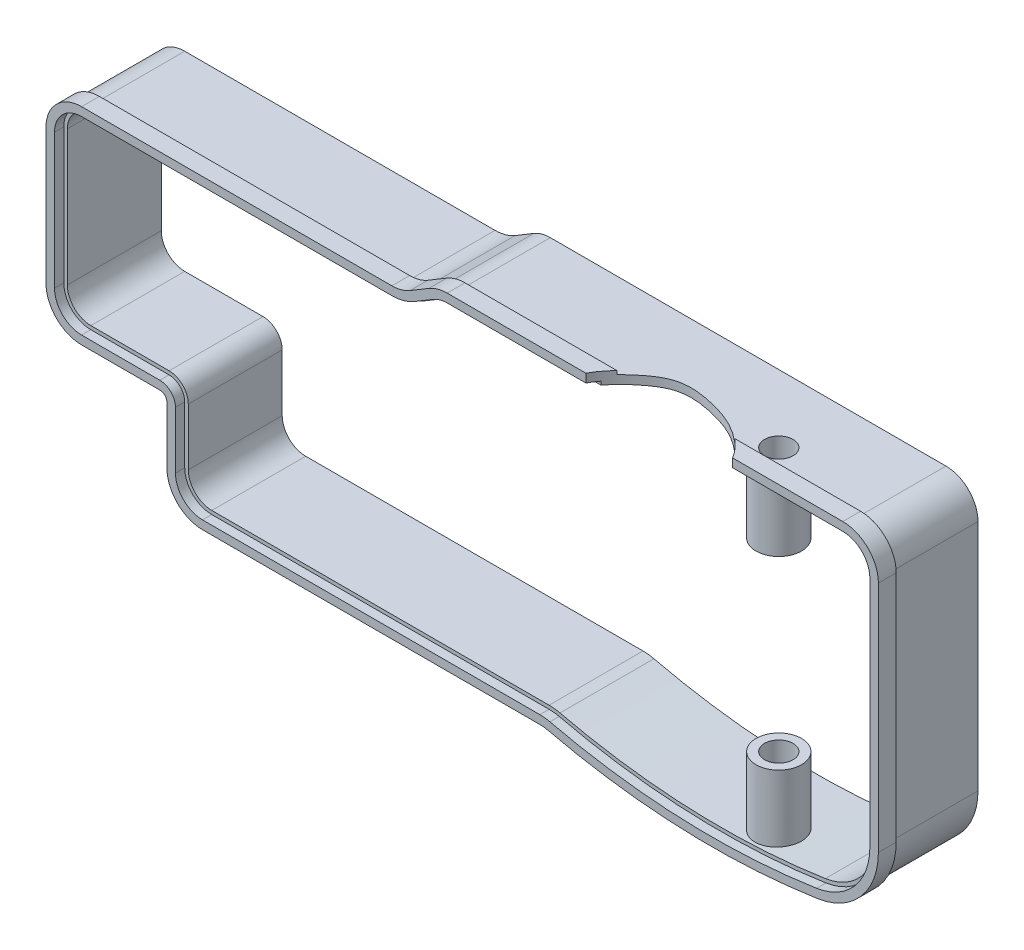
SolidWorks part; units mm, degrees
ref_plane "前视基准面" through (0, 0, 0) normal (0, 0, 1) x (1, 0, 0)
ref_plane "上视基准面" through (0, 0, 0) normal (0, 1, 0) x (1, 0, 0)
ref_plane "右视基准面" through (0, 0, 0) normal (1, 0, 0) x (0, 0, -1)
sketch "草图1" plane through (0, 0, 0) normal (0, 0, 1) x (1, 0, 0)
  line L0 (17, 0) -> (17, 14)
  line L1 (17, 0) -> (70, 0)
  line L2 (0, 14) -> (0, 43)
  line L3 (0, 43) -> (50, 43)
  line L4 (117, 0) -> (117, 43)
  line L5 (17, 14) -> (0, 14)
  line L6 (50, 43) -> (55, 46)
  line L7 (55, 46) -> (117, 46)
  line L8 (117, 46) -> (117, 43)
  arc A0 (70, 0) -> (117, 0) centre (93.5, 97.1995) ccw
  dimension "D4" = 100
  dimension "D2" = 117
  dimension "D5" = 17
  dimension "D6" = 14
  dimension "D7" = 46
  dimension "D8" = 50
  dimension "D9" = 62
extrude "凸台-拉伸1" add sketch "草图1" along normal blind 2.5
fillet "圆角1" radius 5 4 edges at (17, 0, 1.25) (0, 14, 1.25) (0, 43, 1.25) (117, 46, 1.25)
fillet "圆角2" radius 10 1 edges at (117, 0, 1.25)
fillet "圆角3" radius 5 3 edges at (70, 0, 1.25) (50, 43, 1.25) (55, 46, 1.25)
fillet "圆角4" radius 1 1 edges at (17, 14, 1.25)
sketch "草图2" plane through (0, 0, 0) normal (0, 0, -1) x (-1, 0, 0)
  line L16 (-51.4448, 43.2838) -> (-54.0697, 44.8587)
  line L17 (-56.3849, 45.5) -> (-112, 45.5)
  line L18 (-116.5, 41) -> (-116.5, 8.2178)
  line L19 (-69.4115, 0.5) -> (-22, 0.5)
  line L20 (-17.5, 5) -> (-17.5, 13)
  line L21 (-16, 14.5) -> (-5, 14.5)
  line L22 (-0.5, 19) -> (-0.5, 38)
  line L23 (-5, 42.5) -> (-48.6151, 42.5)
  line L24 (-51.4448, 43.2838) -> (-54.0697, 44.8587)
  line L25 (-56.3849, 45.5) -> (-112, 45.5)
  line L26 (-116.5, 41) -> (-116.5, 8.2178)
  line L27 (-69.4115, 0.5) -> (-22, 0.5)
  line L28 (-17.5, 5) -> (-17.5, 13)
  line L29 (-16, 14.5) -> (-5, 14.5)
  line L30 (-0.5, 19) -> (-0.5, 38)
  line L31 (-5, 42.5) -> (-48.6151, 42.5)
  arc A20 (-54.0697, 44.8587) -> (-56.3849, 45.5) centre (-56.3849, 41) ccw
  arc A21 (-112, 45.5) -> (-116.5, 41) centre (-112, 41) ccw
  arc A22 (-116.5, 8.2178) -> (-108.425, -1.1747) centre (-107, 8.2178) ccw
  arc A23 (-108.425, -1.1747) -> (-70.6733, 0.3533) centre (-93.5, 97.1995) ccw
  arc A24 (-69.4115, 0.5) -> (-70.6733, 0.3533) centre (-69.4115, -5) ccw
  arc A25 (-22, 0.5) -> (-17.5, 5) centre (-22, 5) ccw
  arc A26 (-16, 14.5) -> (-17.5, 13) centre (-16, 13) ccw
  arc A27 (-5, 14.5) -> (-0.5, 19) centre (-5, 19) ccw
  arc A28 (-0.5, 38) -> (-5, 42.5) centre (-5, 38) ccw
  arc A29 (-51.4448, 43.2838) -> (-48.6151, 42.5) centre (-48.6151, 48) ccw
  arc A30 (-54.0697, 44.8587) -> (-56.3849, 45.5) centre (-56.3849, 41) ccw
  arc A31 (-112, 45.5) -> (-116.5, 41) centre (-112, 41) ccw
  arc A32 (-116.5, 8.2178) -> (-108.425, -1.1747) centre (-107, 8.2178) ccw
  arc A33 (-108.425, -1.1747) -> (-70.6733, 0.3533) centre (-93.5, 97.1995) ccw
  arc A34 (-69.4115, 0.5) -> (-70.6733, 0.3533) centre (-69.4115, -5) ccw
  arc A35 (-22, 0.5) -> (-17.5, 5) centre (-22, 5) ccw
  arc A36 (-16, 14.5) -> (-17.5, 13) centre (-16, 13) ccw
  arc A37 (-5, 14.5) -> (-0.5, 19) centre (-5, 19) ccw
  arc A38 (-0.5, 38) -> (-5, 42.5) centre (-5, 38) ccw
  arc A39 (-51.4448, 43.2838) -> (-48.6151, 42.5) centre (-48.6151, 48) ccw
  dimension "D1" = 0.5
extrude "凸台-拉伸2" add sketch "草图2" along normal blind 12
sketch "草图3" plane through (0, 45.5, 0) normal (0, 1, 0) x (1, 0, 0)
  line L0 (112, -2.5) -> (56.3849, -2.5) construction
  line L1 (117, 0) -> (117, -2.5) construction
  circle A0 centre (98, 2.5) radius 2
  dimension "D1" = 4
  dimension "D3" = 19
  dimension "D2" = 5
extrude "切除-拉伸1" cut sketch "草图3" against normal through all
shell "抽壳1" thickness 1.2
sketch "草图4" plane through (0, 0, 1.3) normal (0, 0, -1) x (-1, 0, 0)
  line L8 (-56.3849, 44.8) -> (-112, 44.8)
  line L9 (-115.8, 41) -> (-115.8, 8.2178)
  line L10 (-69.4115, 1.2) -> (-22, 1.2)
  line L11 (-18.2, 5) -> (-18.2, 13)
  line L12 (-16, 15.2) -> (-5, 15.2)
  line L13 (-1.2, 19) -> (-1.2, 38)
  line L14 (-5, 41.8) -> (-48.6151, 41.8)
  line L15 (-51.805, 42.6835) -> (-54.4298, 44.2585)
  line L16 (-56.3849, 44.8) -> (-112, 44.8)
  line L17 (-115.8, 41) -> (-115.8, 8.2178)
  line L18 (-69.4115, 1.2) -> (-22, 1.2)
  line L19 (-18.2, 5) -> (-18.2, 13)
  line L20 (-16, 15.2) -> (-5, 15.2)
  line L21 (-1.2, 19) -> (-1.2, 38)
  line L22 (-5, 41.8) -> (-48.6151, 41.8)
  line L23 (-51.805, 42.6835) -> (-54.4298, 44.2585)
  arc A10 (-112, 44.8) -> (-115.8, 41) centre (-112, 41) ccw
  arc A11 (-115.8, 8.2178) -> (-108.32, -0.4826) centre (-107, 8.2178) ccw
  arc A12 (-108.32, -0.4826) -> (-70.8339, 1.0346) centre (-93.5, 97.1995) ccw
  arc A13 (-69.4115, 1.2) -> (-70.8339, 1.0346) centre (-69.4115, -5) ccw
  arc A14 (-22, 1.2) -> (-18.2, 5) centre (-22, 5) ccw
  arc A15 (-16, 15.2) -> (-18.2, 13) centre (-16, 13) ccw
  arc A16 (-5, 15.2) -> (-1.2, 19) centre (-5, 19) ccw
  arc A17 (-1.2, 38) -> (-5, 41.8) centre (-5, 38) ccw
  arc A18 (-51.805, 42.6835) -> (-48.6151, 41.8) centre (-48.6151, 48) ccw
  arc A19 (-54.4298, 44.2585) -> (-56.3849, 44.8) centre (-56.3849, 41) ccw
  arc A20 (-112, 44.8) -> (-115.8, 41) centre (-112, 41) ccw
  arc A21 (-115.8, 8.2178) -> (-108.32, -0.4826) centre (-107, 8.2178) ccw
  arc A22 (-108.32, -0.4826) -> (-70.8339, 1.0346) centre (-93.5, 97.1995) ccw
  arc A23 (-69.4115, 1.2) -> (-70.8339, 1.0346) centre (-69.4115, -5) ccw
  arc A24 (-22, 1.2) -> (-18.2, 5) centre (-22, 5) ccw
  arc A25 (-16, 15.2) -> (-18.2, 13) centre (-16, 13) ccw
  arc A26 (-5, 15.2) -> (-1.2, 19) centre (-5, 19) ccw
  arc A27 (-1.2, 38) -> (-5, 41.8) centre (-5, 38) ccw
  arc A28 (-51.805, 42.6835) -> (-48.6151, 41.8) centre (-48.6151, 48) ccw
  arc A29 (-54.4298, 44.2585) -> (-56.3849, 44.8) centre (-56.3849, 41) ccw
  dimension "D1" = 0
extrude "切除-拉伸2" cut sketch "草图4" against normal through all
sketch "草图5" plane through (0, 0, 2.5) normal (0, 0, 1) x (1, 0, 0)
  line L0 (112, 46) -> (56.3849, 46) construction
  line L1 (79.1953, 34.5) -> (109.1042, 34.5)
  line L2 (79.1953, 34.5) -> (79.1953, 8.5)
  line L3 (79.1953, 8.5) -> (109.1042, 8.5)
  line L4 (109.1042, 34.5) -> (109.1042, 8.5)
  dimension "D1" = 11.5
  dimension "D2" = 26
extrude "切除-拉伸3" cut sketch "草图5" against normal blind 12
sketch "草图6" plane through (0, 46, 0) normal (0, 1, 0) x (1, 0, 0)
  spline S0 degree 3 poles (71.0943, -10.0246) (103.8497, -9.3957) (93.2311, 1.4451) (88.1301, 3.3043) (82.9063, 4.0739) (79.3274, 1.5601) (76.9251, -0.689) (71.0943, -10.0246) (103.8497, -9.3957) (93.2311, 1.4451) knots -0.572635 -0.506756 -0.437414 0 0.133194 0.239246 0.354041 0.427365 0.493244 0.562586 1 1.133194 1.239246 1.354041 only from (96.9964, -4.0542) to (96.9964, -4.0542)
extrude "切除-拉伸4" cut sketch "草图6" against normal blind 25
